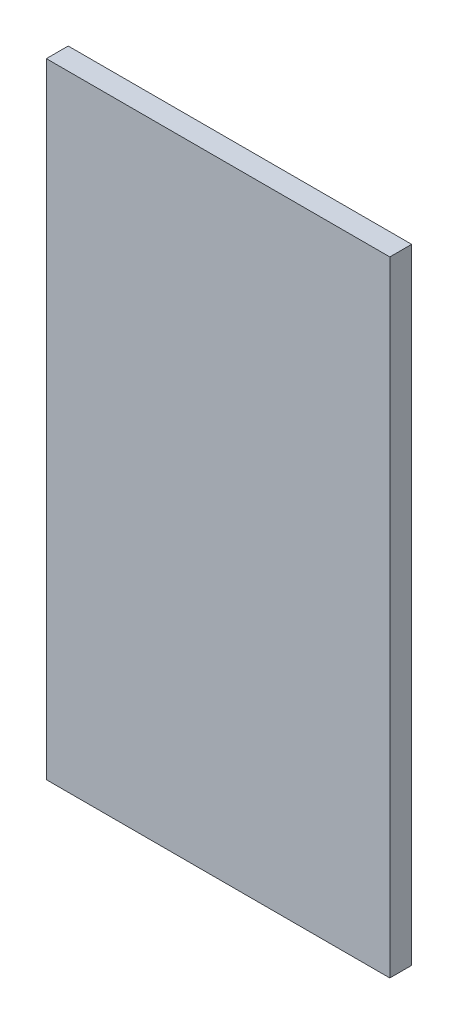
SolidWorks part; units mm, degrees
ref_plane "前视基准面" through (0, 0, 0) normal (0, 0, 1) x (1, 0, 0)
ref_plane "上视基准面" through (0, 0, 0) normal (0, 1, 0) x (1, 0, 0)
ref_plane "右视基准面" through (0, 0, 0) normal (1, 0, 0) x (0, 0, -1)
other "Configuration Table"
sketch "草图1" plane through (0, 0, 0) normal (0, 0, 1) x (1, 0, 0)
  line L1 (0, 0) -> (110, 0)
  line L2 (0, 0) -> (0, 200)
  line L3 (0, 200) -> (110, 200)
  line L4 (110, 0) -> (110, 200)
  dimension "D1" = 200
  dimension "D2" = 110
extrude "凸台-拉伸1" add sketch "草图1" along normal blind 7 contours L4 L3 L2 L1
